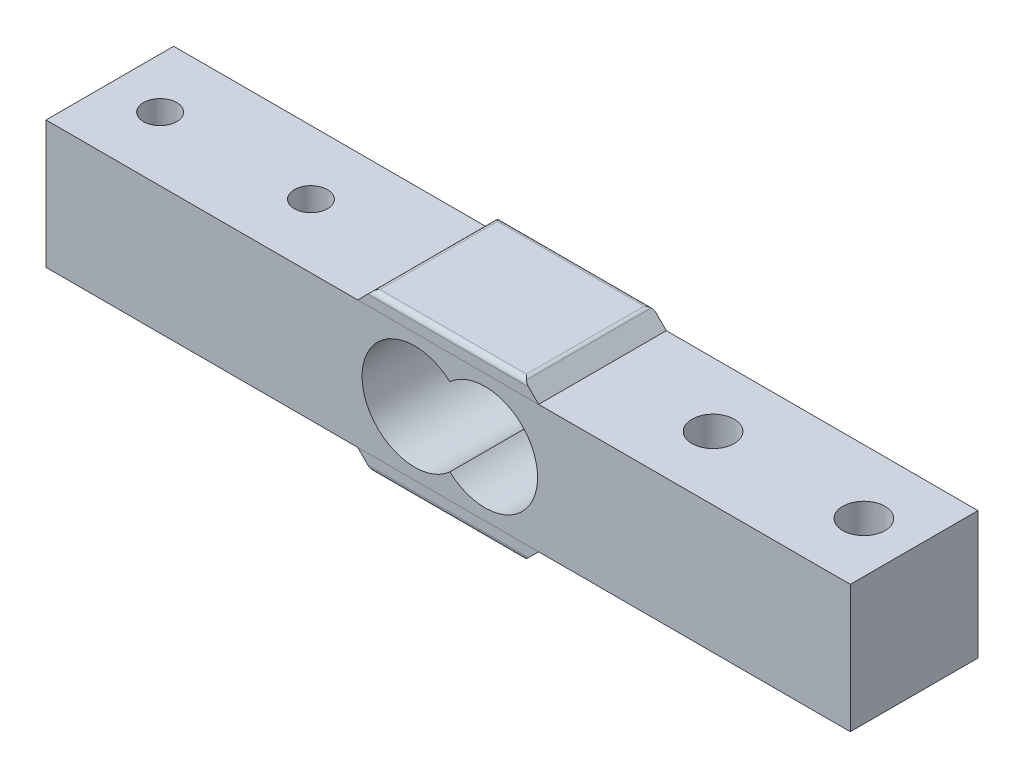
SolidWorks part; units mm, degrees
material "1100-H12 Barra (SS)"
ref_plane "Alzado" through (0, 0, 0) normal (0, 0, 1) x (1, 0, 0)
ref_plane "Planta" through (0, 0, 0) normal (0, 1, 0) x (1, 0, 0)
ref_plane "Vista lateral" through (0, 0, 0) normal (1, 0, 0) x (0, 0, -1)
sketch "Croquis1" plane through (0, 0, 0) normal (0, 0, 1) x (1, 0, 0)
  line L1 (-40, 6.35) -> (40, 6.35)
  line L2 (-40, 6.35) -> (-40, -6.35)
  line L3 (-40, -6.35) -> (40, -6.35)
  line L4 (40, 6.35) -> (40, -6.35)
  point P4 (0, 6.35)
  point P6 (-40, 0)
  dimension "D1" = 80
  dimension "D2" = 12.7
extrude "Saliente-Extruir1" add sketch "Croquis1" along normal mid plane 12.7
sketch "Croquis2" plane through (0, 0, 6.35) normal (0, 0, 1) x (1, 0, 0)
  circle A0 centre (-3.3336, 0) radius 5.23
  circle A1 centre (3.6664, 0) radius 5.23
  dimension "D2" = 10.46
  dimension "D1" = 7
extrude "Cortar-Extruir1" cut sketch "Croquis2" against normal through all contours A1 A0 | A0 A1 | A0 A1
hole_wizard "Taladro roscado M5x0.81" positions "Croquis3" profile "Croquis4" tap size "M5x0.8" standard "Ansi Metric" end condition through all
sketch "Croquis3" plane through (0, 6.35, 0) normal (0, 1, 0) x (1, 0, 0)
  line L0 (40, -6.35) -> (40, 6.35) construction
  point P0 (20, 0)
  point P2 (35, 0)
  dimension "D1" = 15
  dimension "D2" = 5
sketch "Croquis4" plane through (20, 6.35, 0) normal (1, 0, 0) x (0, 0, 1)
  line L0 (0, 0) -> (0, 12.7)
  line L1 (0, 12.7) -> (2.1, 12.7)
  line L2 (2.1, 12.7) -> (2.1, 0)
  line L5 (2.1, 0) -> (0, 0)
  line L11 (0, -6.35) -> (0, 107.95) construction
  dimension "Diámetro de perforador para roscar hasta el siguiente" = 4.2
  dimension "Profundidad de perforador para roscar hasta el siguiente" = 12.7
cosmetic thread "Rosca de taladro1" parameters "D2"=5
cosmetic thread "Rosca de taladro2" parameters "D2"=5
hole_wizard "Taladro roscado M4x0.71" positions "Croquis5" profile "Croquis6" tap size "M4x0.7" standard "Ansi Metric" end condition through all
sketch "Croquis5" plane through (0, 6.35, 0) normal (0, 1, 0) x (1, 0, 0)
  line L0 (-40, -6.35) -> (-40, 6.35) construction
  point P0 (-35, 0)
  point P2 (-20, 0)
  dimension "D1" = 15
  dimension "D2" = 5
sketch "Croquis6" plane through (-35, 6.35, 0) normal (1, 0, 0) x (0, 0, 1)
  line L0 (0, 0) -> (0, 12.7)
  line L1 (0, 12.7) -> (1.65, 12.7)
  line L2 (1.65, 12.7) -> (1.65, 0)
  line L5 (1.65, 0) -> (0, 0)
  line L11 (0, -6.35) -> (0, 107.95) construction
  dimension "Diámetro de perforador para roscar hasta el siguiente" = 3.3
  dimension "Profundidad de perforador para roscar hasta el siguiente" = 12.7
cosmetic thread "Rosca de taladro3" parameters "D2"=4
cosmetic thread "Rosca de taladro4" parameters "D2"=4
sketch "Croquis7" plane through (-40, 0, 0) normal (-1, 0, 0) x (0, 0, 1)
  text T0 "5kg"
extrude "Cortar-Extruir2" cut sketch "Croquis7" against normal blind 0.01
sketch "Croquis8" plane through (0, 0, 6.35) normal (0, 0, 1) x (1, 0, 0)
  line L0 (-9, 6.35) -> (-7.5, 7.85)
  line L1 (40, 6.35) -> (-40, 6.35) construction
  line L2 (-7.5, 7.85) -> (7.5, 7.85)
  line L3 (7.5, 7.85) -> (9, 6.35)
  line L4 (-9, 6.35) -> (9, 6.35)
  point P4 (0, 6.35)
  point P7 (0, 7.85)
  dimension "D1" = 45
  dimension "D2" = 1.5
  dimension "D3" = 18
extrude "Saliente-Extruir2" add sketch "Croquis8" against normal up to surface (12.7 mm away) separate body up to face at (0.1664, 0, -6.35)
fillet "Redondeo1" radius 0.5 4 edges at (7.5, 7.85, 0) (0, 7.85, 6.35) (-7.5, 7.85, 0) (0, 7.85, -6.35)
mirror "Simetría2" about plane through (0, 0, 0) normal (0, 1, 0) of bodies 106
